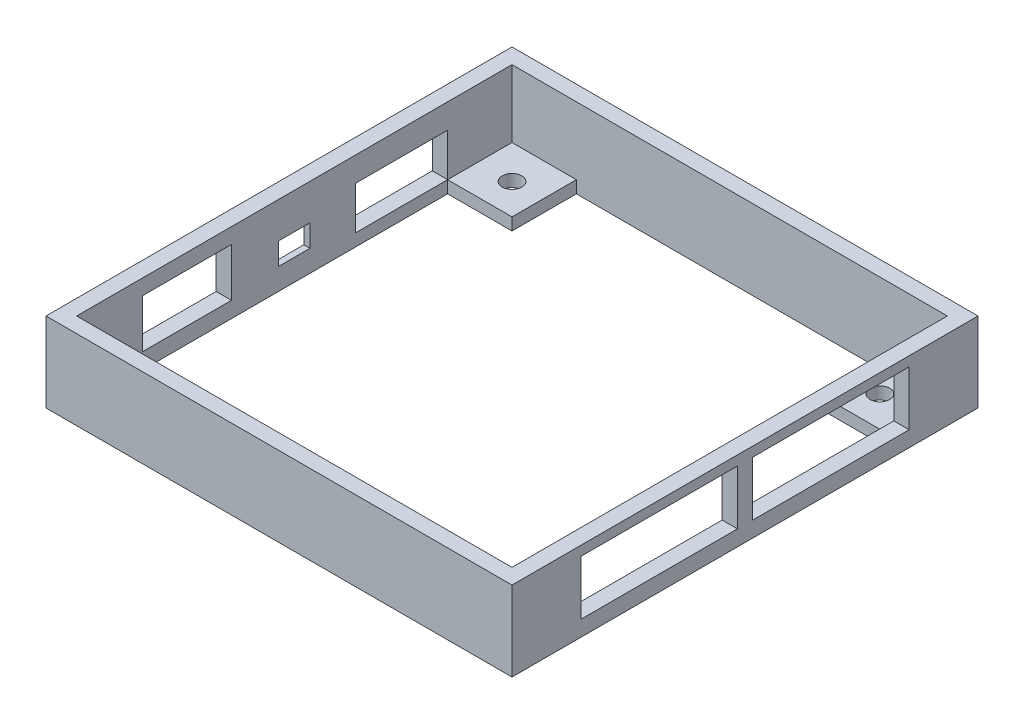
SolidWorks part; units mm, degrees
ref_plane "前视基准面" through (0, 0, 0) normal (0, 0, 1) x (1, 0, 0)
ref_plane "上视基准面" through (0, 0, 0) normal (0, 1, 0) x (1, 0, 0)
ref_plane "右视基准面" through (0, 0, 0) normal (1, 0, 0) x (0, 0, -1)
sketch "草图1" plane through (0, 0, 0) normal (0, 1, 0) x (1, 0, 0)
  line L1 (38, -38) -> (-38, -38)
  line L2 (38, -38) -> (38, 38)
  line L3 (38, 38) -> (-38, 38)
  line L4 (-38, -38) -> (-38, 38)
  line L5 (38, -38) -> (-38, 38) construction
  line L6 (38, 38) -> (-38, -38) construction
  point P0 (0, 0)
  dimension "D1" = 76
  dimension "D2" = 76
extrude "凸台-拉伸1" add sketch "草图1" along normal blind 13
sketch "草图2" plane through (0, 13, 0) normal (0, 1, 0) x (1, 0, 0)
  line L1 (35.5, -35.5) -> (-35.5, -35.5)
  line L2 (35.5, -35.5) -> (35.5, 35.5)
  line L3 (35.5, 35.5) -> (-35.5, 35.5)
  line L4 (-35.5, -35.5) -> (-35.5, 35.5)
  line L5 (35.5, -35.5) -> (-35.5, 35.5) construction
  line L6 (35.5, 35.5) -> (-35.5, -35.5) construction
  point P0 (0, 0)
  dimension "D1" = 71
  dimension "D2" = 71
extrude "切除-拉伸1" cut sketch "草图2" against normal blind 11
sketch "草图3" plane through (0, 2, 0) normal (0, 1, 0) x (1, 0, 0)
  line L1 (30, -30) -> (-30, -30) construction
  line L2 (30, -30) -> (30, 30) construction
  line L3 (30, 30) -> (-30, 30) construction
  line L4 (-30, -30) -> (-30, 30) construction
  line L5 (30, -30) -> (-30, 30) construction
  line L6 (30, 30) -> (-30, -30) construction
  circle A0 centre (-30, 30) radius 1.6
  point P0 (0, 0)
  dimension "D3" = 3.2
  dimension "D1" = 60
  dimension "D2" = 60
extrude "切除-拉伸2" cut sketch "草图3" against normal through all
pattern_linear "阵列(线性)1" count 2 spacing 60 along (1, 0, 0) count 2 spacing 60 along (0, 0, 1) of "切除-拉伸2"
sketch "草图4" plane through (0, 2, 0) normal (0, 1, 0) x (1, 0, 0)
  line L0 (-35.5, 35.5) -> (-35.5, -35.5) construction
  line L1 (35.5, -25) -> (25, -25)
  line L2 (35.5, -25) -> (35.5, 25)
  line L3 (35.5, 25) -> (25, 25)
  line L4 (-35.5, -25) -> (-35.5, 25)
  line L5 (35.5, -25) -> (-35.5, 25) construction
  line L6 (35.5, 25) -> (-35.5, -25) construction
  line L7 (35.5, 35.5) -> (-35.5, 35.5) construction
  line L8 (25, -35.5) -> (-25, -35.5)
  line L9 (25, -35.5) -> (25, -25)
  line L10 (25, 35.5) -> (-25, 35.5)
  line L11 (-25, -35.5) -> (-25, -25)
  line L12 (25, -35.5) -> (-25, 35.5) construction
  line L13 (25, 35.5) -> (-25, -35.5) construction
  line L14 (-25, 25) -> (-35.5, 25)
  line L15 (-25, 25) -> (-25, 35.5)
  line L16 (-25, -25) -> (-35.5, -25)
  line L17 (25, 25) -> (25, 35.5)
  point P0 (0, 0)
  point P8 (0, 0)
  dimension "D1" = 50
  dimension "D2" = 50
extrude "切除-拉伸3" cut sketch "草图4" against normal through all
sketch "草图5" plane through (-38, 0, 0) normal (-1, 0, 0) x (0, 0, 1)
  line L0 (23.7501, 9.4862) -> (21.7501, 9.4862) construction
  line L1 (11.2501, 3.5862) -> (23.7501, 3.5862) construction
  line L2 (11.2501, 3.5862) -> (11.2501, 9.4862) construction
  line L3 (11.2501, 9.4862) -> (23.7501, 9.4862) construction
  line L4 (23.7501, 3.5862) -> (23.7501, 9.4862) construction
  line L5 (10.2501, 2.5862) -> (10.2501, 10.4862)
  line L6 (10.2501, 10.4862) -> (24.7501, 10.4862)
  line L7 (24.7501, 2.5862) -> (24.7501, 10.4862)
  line L8 (10.2501, 2.5862) -> (24.7501, 2.5862)
  dimension "D1" = 1
extrude "切除-拉伸5" cut sketch "草图5" against normal up to next
sketch "草图7" plane through (38, 0, 0) normal (1, 0, 0) x (0, 0, -1)
  line L0 (26.7713, 11.4276) -> (26.7713, 2.5447)
  line L5 (25.7713, 10.4276) -> (2.2284, 10.4276) construction
  line L6 (25.7713, 10.4276) -> (25.7713, 3.5447) construction
  line L7 (25.7713, 3.5447) -> (2.2284, 3.5447) construction
  line L8 (2.2284, 10.4276) -> (2.2284, 3.5447) construction
  line L9 (26.7713, 2.5447) -> (1.2284, 2.5447)
  line L10 (1.2284, 11.4276) -> (1.2284, 2.5447)
  line L11 (26.7713, 11.4276) -> (1.2284, 11.4276)
  line L12 (-1.2288, 11.4276) -> (-1.2288, 2.5447)
  line L13 (-2.2288, 10.4276) -> (-25.7716, 10.4276) construction
  line L14 (-2.2288, 10.4276) -> (-2.2288, 3.5447) construction
  line L15 (-2.2288, 3.5447) -> (-25.7716, 3.5447) construction
  line L16 (-25.7716, 10.4276) -> (-25.7716, 3.5447) construction
  line L17 (-1.2288, 2.5447) -> (-26.7716, 2.5447)
  line L18 (-26.7716, 11.4276) -> (-26.7716, 2.5447)
  line L19 (-1.2288, 11.4276) -> (-26.7716, 11.4276)
  arc A0 (25.8298, 10.2862) -> (25.6298, 10.4862) centre (25.6298, 10.2862) ccw construction
  arc A1 (2.1698, 3.6862) -> (2.3698, 3.4862) centre (2.3698, 3.6862) ccw construction
  arc A2 (-2.1702, 10.2862) -> (-2.3702, 10.4862) centre (-2.3702, 10.2862) ccw construction
  arc A3 (-25.8302, 3.6862) -> (-25.6302, 3.4862) centre (-25.6302, 3.6862) ccw construction
  dimension "D1" = 1
  dimension "D2" = 1
extrude "切除-拉伸6" cut sketch "草图7" against normal up to next
sketch "草图8" plane through (-35.5, 0, 0) normal (1, 0, 0) x (0, 0, -1)
  line L0 (2.55, 3.5362) -> (2.55, 7.1362)
  line L1 (1.55, 4.5362) -> (-1.55, 4.5362) construction
  line L2 (1.55, 4.5362) -> (1.55, 6.1362) construction
  line L3 (1.55, 6.1362) -> (-1.55, 6.1362) construction
  line L4 (-1.55, 4.5362) -> (-1.55, 6.1362) construction
  line L5 (2.55, 7.1362) -> (-2.55, 7.1362)
  line L6 (-2.55, 3.5362) -> (-2.55, 7.1362)
  line L7 (2.55, 3.5362) -> (-2.55, 3.5362)
  dimension "D1" = 1
extrude "切除-拉伸7" cut sketch "草图8" against normal up to next
sketch "草图9" plane through (-35.5, 0, 0) normal (1, 0, 0) x (0, 0, -1)
  line L0 (-30.0001, 2) -> (30, 2) construction
  line L1 (25, 2) -> (10, 2)
  line L2 (25, 2) -> (25, 9)
  line L3 (25, 9) -> (10, 9)
  line L4 (10, 2) -> (10, 9)
  line L5 (38, 13) -> (38, 0) construction
  dimension "D1" = 7
  dimension "D2" = 15
  dimension "D3" = 13
extrude "切除-拉伸8" cut sketch "草图9" against normal up to next
chamfer "倒角1" distance 1.5 angle 45 4 edges at (-38, 5.3362, 2.55) (-38, 7.1362, 0) (-38, 3.5362, 0) (-38, 5.3362, -2.55)
